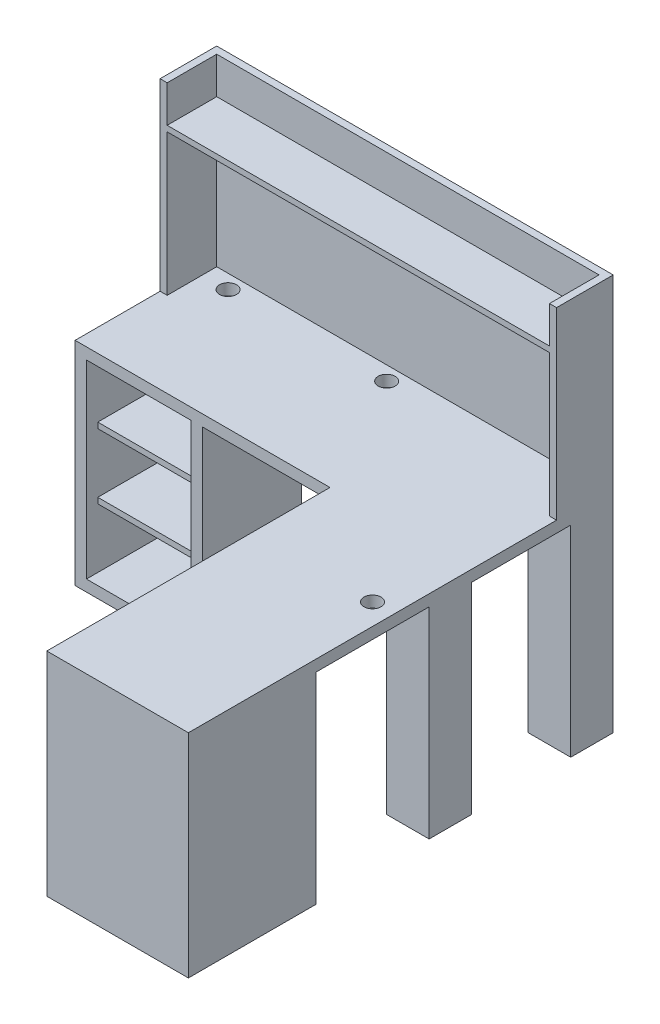
SolidWorks part; units mm, degrees
ref_plane "Front Plane" through (0, 0, 0) normal (0, 0, 1) x (1, 0, 0)
ref_plane "Top Plane" through (0, 0, 0) normal (0, 1, 0) x (1, 0, 0)
ref_plane "Right Plane" through (0, 0, 0) normal (1, 0, 0) x (0, 0, -1)
sketch "Sketch2" plane through (0, 0, 0) normal (0, 1, 0) x (1, 0, 0)
  line L0 (900, 0) -> (1400, 500)
  line L1 (0, 0) -> (900, 0)
  line L2 (0, 0) -> (0, 500)
  line L3 (0, 500) -> (1400, 500)
  line L4 (1400, 0) -> (1400, 500)
  line L6 (1400, 0) -> (1400, -1000)
  line L7 (1400, -1000) -> (900, -1000)
  line L8 (900, 0) -> (900, -1000)
  dimension "D1" = 500
  dimension "D2" = 1400
  dimension "D3" = 1000
  dimension "D4" = 500
extrude "Boss-Extrude1" add sketch "Sketch2" along normal blind 40 contours L3 L2 L1 L0 | L0 L8 L7 L6 L4
sketch "Sketch3" plane through (0, 0, 0) normal (0, -1, 0) x (1, 0, 0)
  line L0 (0, -500) -> (1400, -500) construction
  line L1 (0, 0) -> (450, 0)
  line L2 (0, 0) -> (0, -500)
  line L3 (0, -500) -> (450, -500)
  line L4 (450, 0) -> (450, -500)
  line L5 (1400, -500) -> (1400, 1000) construction
  line L6 (900, 1000) -> (1400, 1000)
  line L7 (900, 1000) -> (900, 550)
  line L8 (900, 550) -> (1400, 550)
  line L9 (1400, 1000) -> (1400, 550)
  dimension "D1" = 450
  dimension "D2" = 450
extrude "Boss-Extrude2" add sketch "Sketch3" along normal blind 710
sketch "Sketch4" plane through (0, 40, 0) normal (0, 1, 0) x (1, 0, 0)
  line L0 (900, 0) -> (1400, 500)
sketch "Sketch5" plane through (0, 0, -500) normal (0, 0, -1) x (-1, 0, 0)
  line L0 (770, 0) -> (-770, 0) construction
  line L1 (-450, -710) -> (-40, -710)
  line L2 (-450, -710) -> (-450, 0)
  line L3 (-450, 0) -> (-40, 0)
  line L4 (-40, -710) -> (-40, 0)
  dimension "D1" = 410
extrude "Cut-Extrude1" cut sketch "Sketch5" against normal blind 150
sketch "Sketch7" plane through (0, 0, 0) normal (0, -1, 0) x (1, 0, 0)
  line L0 (40, -350) -> (450, -350) construction
  line L1 (40, -500) -> (190, -500) construction
  line L2 (40, -500) -> (40, -350) construction
  line L3 (40, -350) -> (190, -350) construction
  line L4 (190, -500) -> (190, -350) construction
  line L5 (40, -350) -> (190, -500) construction
  line L6 (900, 0) -> (450, 0)
  line L7 (675, 0) -> (675, -75)
  line L8 (900, 0) -> (900, 550)
  line L9 (900, 275) -> (975, 275)
  line L10 (975, 275) -> (1325, 275)
  line L11 (675, -75) -> (675, -425)
  circle A0 centre (115, -425) radius 30
  circle A1 centre (675, -425) radius 30
  circle A2 centre (1325, 275) radius 30
  dimension "D2" = 75
  dimension "D1" = 150
  dimension "D3" = 75
  dimension "D4" = 350
extrude "Cut-Extrude2" cut sketch "Sketch7" against normal blind 150
sketch "Sketch8" plane through (0, 0, 0) normal (0, 0, 1) x (1, 0, 0)
  line L0 (0, 40) -> (900, 40) construction
  line L1 (0, -710) -> (450, -710)
  line L2 (0, -710) -> (0, 40)
  line L3 (0, 40) -> (450, 40)
  line L4 (450, -710) -> (450, 40)
  line L5 (40, -670) -> (40, 0)
  line L6 (40, 0) -> (410, 0)
  line L7 (410, -670) -> (410, 0)
  line L8 (40, -670) -> (410, -670)
  dimension "D1" = 40
extrude "Cut-Extrude3" cut sketch "Sketch8" against normal blind 310 contours L5 L6 L7 L8
sketch "Sketch9" plane through (900, 0, 0) normal (-1, 0, 0) x (0, 0, 1)
  line L0 (590, -670) -> (590, 0)
  line L1 (550, -710) -> (1000, -710)
  line L2 (550, -710) -> (550, 40)
  line L3 (550, 40) -> (1000, 40)
  line L4 (1000, -710) -> (1000, 40)
  line L5 (590, 0) -> (960, 0)
  line L6 (960, -670) -> (960, 0)
  line L7 (590, -670) -> (960, -670)
  dimension "D1" = 40
extrude "Cut-Extrude4" cut sketch "Sketch9" against normal blind 460 contours L0 L5 L6 L7
sketch "Sketch10" plane through (0, 0, 0) normal (0, -1, 0) x (1, 0, 0)
  line L0 (900, 0) -> (1400, -500) construction
  line L1 (1400, -500) -> (1250, -500)
  line L2 (1400, -500) -> (1400, -350)
  line L3 (1400, -350) -> (1250, -350)
  line L4 (1250, -500) -> (1250, -350)
  line L5 (900, 0) -> (1400, 0)
  line L6 (1400, -500) -> (1400, 550) construction
  line L8 (1400, 0) -> (1250, 0)
  line L9 (1400, 0) -> (1400, 150)
  line L10 (1400, 150) -> (1250, 150)
  line L11 (1250, 0) -> (1250, 150)
  line M14 (40, -500) -> (1400, -500)
  line M15 (1400, -500) -> (1400, 550)
  dimension "D1" = 150
  dimension "D2" = 150
  dimension "D3" = 150
extrude "Boss-Extrude3" add sketch "Sketch10" along normal blind 710 contours L11 L5 L10 M15 | L4 L3 M14 M15
sketch "Sketch11" plane through (410, 0, 0) normal (-1, 0, 0) x (0, 0, 1)
  line L0 (0, 0) -> (0, -670)
  line L1 (0, -670) -> (0, -460)
  line L2 (-310, -670) -> (-310, 0) construction
  line L3 (0, -460) -> (-310, -460)
  line L4 (0, -460) -> (0, -440)
  line L5 (0, -440) -> (-310, -440)
  line L6 (-310, -460) -> (-310, -440)
  line L7 (0, -440) -> (0, -230)
  line L9 (0, -230) -> (-310, -230)
  line L10 (0, -230) -> (0, -210)
  line L11 (0, -210) -> (-310, -210)
  line L12 (-310, -230) -> (-310, -210)
  line M8 (-310, 0) -> (-310, -670)
  dimension "D1" = 210
  dimension "D2" = 20
  dimension "D3" = 210
  dimension "D4" = 20
extrude "Boss-Extrude4" add sketch "Sketch11" along normal blind 410 contours L0 L11 L9 M8 | L0 L5 L3 M8
sketch "Sketch12" plane through (0, 0, 0) normal (0, 0, 1) x (1, 0, 0)
  line L1 (40, -670) -> (410, -670)
  line L2 (40, -670) -> (40, 0)
  line L3 (40, 0) -> (410, 0)
  line L4 (410, -670) -> (410, 0)
extrude "Cut-Extrude5" cut sketch "Sketch12" against normal blind 40
sketch "Sketch13" plane through (0, 0, 590) normal (0, 0, 1) x (1, 0, 0)
  line L0 (900, 0) -> (900, -335)
  line L1 (900, 40) -> (900, -710) construction
  line L2 (900, -335) -> (900, -350)
  line L3 (1360, -670) -> (1360, 0) construction
  line L4 (900, -350) -> (1360, -350)
  line L5 (900, -350) -> (900, -320)
  line L6 (900, -320) -> (1360, -320)
  line L7 (1360, -350) -> (1360, -320)
  line M3 (900, 0) -> (900, -670)
  line M5 (1360, -670) -> (1360, 0)
  dimension "D1" = 30
extrude "Boss-Extrude5" add sketch "Sketch13" along normal up to surface (370 mm away) contours L6 L0 L4 M3 M5 up to face at (1130, -335, 960)
sketch "Sketch14" plane through (900, 0, 0) normal (-1, 0, 0) x (0, 0, 1)
  line L1 (590, -670) -> (960, -670)
  line L2 (590, -670) -> (590, 0)
  line L3 (590, 0) -> (960, 0)
  line L4 (960, -670) -> (960, 0)
extrude "Cut-Extrude10" cut sketch "Sketch14" against normal blind 40
sketch "Sketch16" plane through (0, 40, 0) normal (0, 1, 0) x (1, 0, 0)
  line L0 (0, 500) -> (1400, 500)
  line L1 (1400, 500) -> (1400, 300)
  line L2 (1400, 500) -> (1400, -1000) construction
  line L3 (0, 500) -> (0, 300)
  line L4 (0, 0) -> (0, 500) construction
  line L5 (1375, 475) -> (1375, 300)
  line L6 (25, 475) -> (1375, 475)
  line L7 (25, 475) -> (25, 300)
  line L8 (0, 300) -> (25, 300)
  line L9 (1375, 300) -> (1400, 300)
  dimension "D1" = 25
extrude "Boss-Extrude6" add sketch "Sketch16" along normal blind 650
sketch "Sketch17" plane through (25, 0, 0) normal (1, 0, 0) x (0, 0, -1)
  line L0 (300, 40) -> (300, 540)
  line L1 (300, 690) -> (300, 40) construction
  line L2 (475, 690) -> (475, 40) construction
  line L3 (300, 540) -> (475, 540)
  line L4 (300, 540) -> (300, 560)
  line L5 (300, 560) -> (475, 560)
  line L6 (475, 540) -> (475, 560)
  dimension "D1" = 20
extrude "Boss-Extrude7" add sketch "Sketch17" along normal up to surface (1350 mm away) contours L4 L5 L6 L3 up to face at (1375, 365, -387.5)
